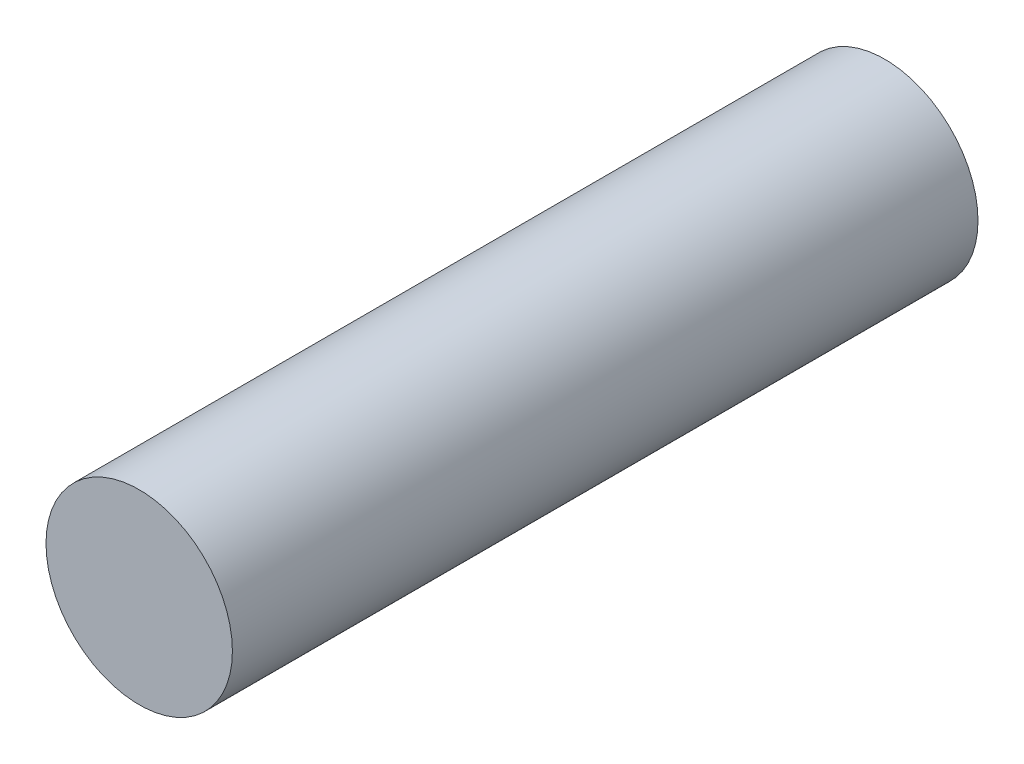
SolidWorks part; units mm, degrees
ref_plane "Front Plane" through (0, 0, 0) normal (0, 0, 1) x (1, 0, 0)
ref_plane "Top Plane" through (0, 0, 0) normal (0, 1, 0) x (1, 0, 0)
ref_plane "Right Plane" through (0, 0, 0) normal (1, 0, 0) x (0, 0, -1)
sketch "Sketch1" plane through (0, 0, 0) normal (0, 0, 1) x (1, 0, 0)
  circle A0 centre (0, 0) radius 3.175
  dimension "D1" = 6.35
extrude "Boss-Extrude1" add sketch "Sketch1" along normal blind 25.4
sketch "Sketch2" plane through (0, 0, 0) normal (0, 0, -1) x (-1, 0, 0)
  circle A0 centre (0, 0) radius 1.016
  dimension "D1" = 2.032
extrude "Cut-Extrude1" cut sketch "Sketch2" against normal blind 5.08
